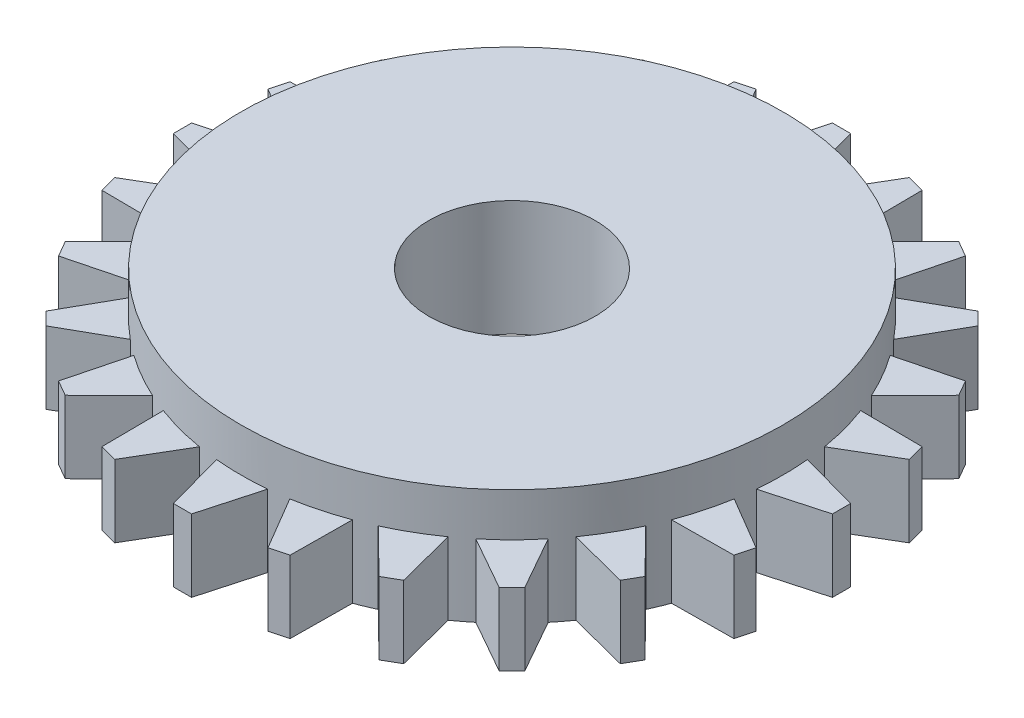
SolidWorks part; units mm, degrees
ref_plane "Front Plane" through (0, 0, 0) normal (0, 0, 1) x (1, 0, 0)
ref_plane "Top Plane" through (0, 0, 0) normal (0, 1, 0) x (1, 0, 0)
ref_plane "Right Plane" through (0, 0, 0) normal (1, 0, 0) x (0, 0, -1)
sketch "Sketch1" plane through (0, 0, 0) normal (0, 1, 0) x (1, 0, 0)
  circle A0 centre (0, 0) radius 2.3
  circle A1 centre (0, 0) radius 7.5
  dimension "D1" = 4.6
  dimension "D2" = 15
extrude "Boss-Extrude1" add sketch "Sketch1" along normal blind 3.2
sketch "Sketch2" plane through (0, 0, 0) normal (0, -1, 0) x (1, 0, 0)
  line L0 (0, 0) -> (7.5, 0) construction
  line L1 (7.5, 0) -> (9.1145, 0) construction
  line L2 (9.1145, 0.25) -> (9.1145, -0.25)
  line L3 (7.3145, -0.75) -> (7.3145, 0.75)
  line L4 (7.3145, 0.75) -> (9.1145, 0.25)
  line L5 (9.1145, -0.25) -> (7.3145, -0.75)
  circle A0 centre (0, 0) radius 7.5 construction
  point P9 (9.1145, 0)
  point P13 (7.3145, 0)
  dimension "D2" = 1.8
  dimension "D3" = 1.5
  dimension "D4" = 0.5
extrude "Boss-Extrude2" add sketch "Sketch2" against normal blind 2
pattern_circular "CirPattern1" count 24 over 360 about axis through (0, 0, 0) along (0, 1, 0) of "Boss-Extrude2"
